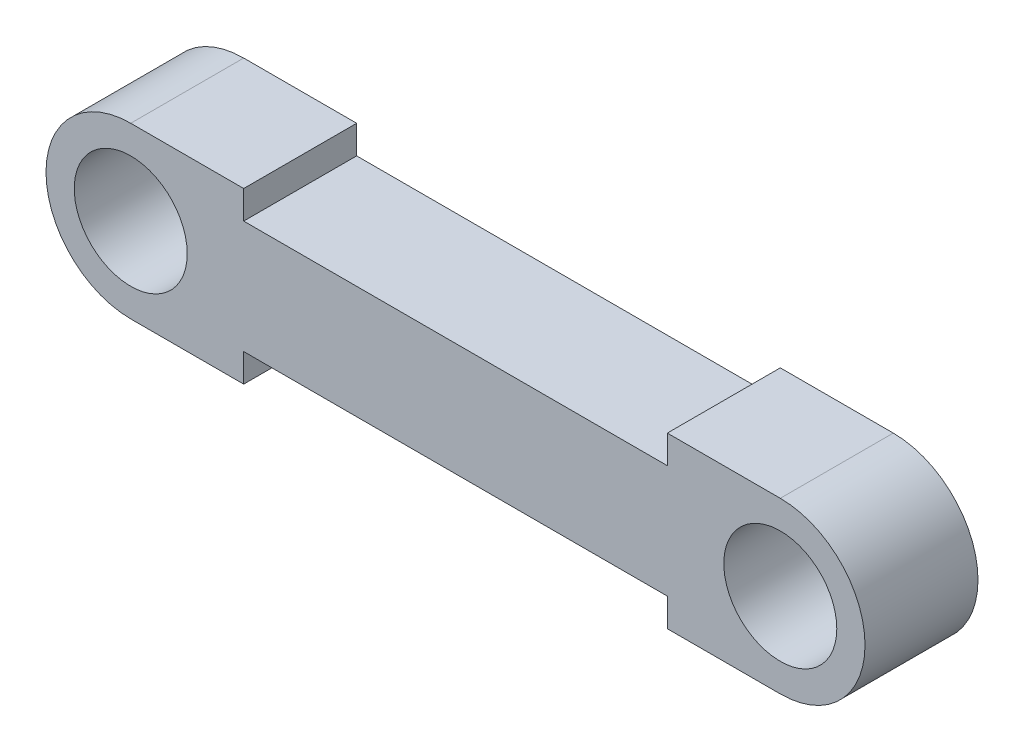
SolidWorks part; units mm, degrees
ref_plane "前视基准面" through (0, 0, 0) normal (0, 0, 1) x (1, 0, 0)
ref_plane "上视基准面" through (0, 0, 0) normal (0, 1, 0) x (1, 0, 0)
ref_plane "右视基准面" through (0, 0, 0) normal (1, 0, 0) x (0, 0, -1)
sketch "草图1" plane through (0, 0, 0) normal (0, 0, 1) x (1, 0, 0)
  line L0 (55, 0) -> (-55, 0) construction
  line L2 (0, 0) -> (23, 0) construction
  line L3 (0, 3) -> (4, 3)
  line L4 (0, -3) -> (4, -3)
  line L5 (4, 3) -> (4, 2)
  line L6 (4, 2) -> (19, 2)
  line L7 (19, 2) -> (19, 3)
  line L8 (19, -2) -> (19, -3)
  line L9 (4, -3) -> (4, -2)
  line L10 (4, -2) -> (19, -2)
  line L11 (19, 3) -> (23, 3)
  line L12 (19, -3) -> (23, -3)
  arc A0 (0, 3) -> (0, -3) centre (0, 0) ccw
  arc A1 (23, -3) -> (23, 3) centre (23, 0) ccw
  circle A2 centre (0, 0) radius 2
  circle A3 centre (23, 0) radius 2
  point P2 (11.5, 0)
extrude "凸台-拉伸1" add sketch "草图1" along normal mid plane 4
